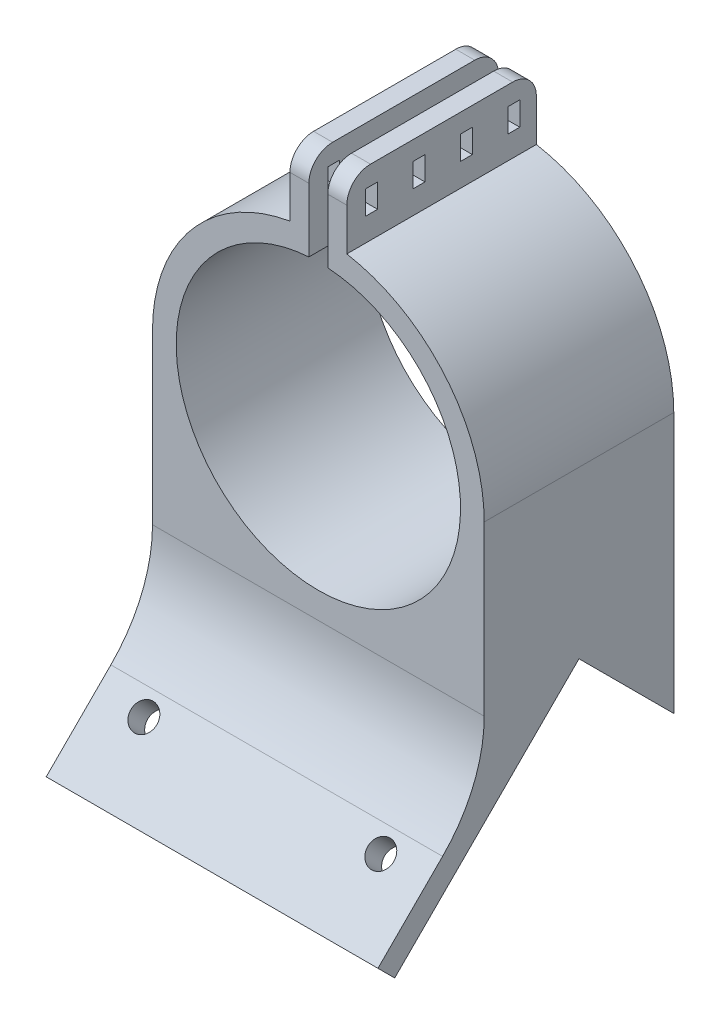
SolidWorks part; units mm, degrees
ref_plane "Plan de face" through (0, 0, 0) normal (0, 0, 1) x (1, 0, 0)
ref_plane "Plan de dessus" through (0, 0, 0) normal (0, 1, 0) x (1, 0, 0)
ref_plane "Plan de droite" through (0, 0, 0) normal (1, 0, 0) x (0, 0, -1)
sketch "Esquisse1" plane through (0, 0, 0) normal (0, 0, 1) x (1, 0, 0)
  circle A0 centre (0, 0) radius 35
  dimension "D1" = 70
extrude "Boss.-Extru.1" add sketch "Esquisse1" along normal blind 40
sketch "Esquisse6" plane through (0, 0, 0) normal (0, 1, 0) x (1, 0, 0)
  line L1 (-35, -40) -> (35, -40)
  line L2 (-35, -40) -> (-35, 0)
  line L3 (-35, 0) -> (35, 0)
  line L4 (35, -40) -> (35, 0)
extrude "Boss.-Extru.3" add sketch "Esquisse6" against normal blind 70
sketch "Esquisse2" plane through (0, 0, 40) normal (0, 0, 1) x (1, 0, 0)
  circle A0 centre (0, 0) radius 30
  dimension "D1" = 60
extrude "Enlèv. mat.-Extru.1" cut sketch "Esquisse2" against normal blind 40
sketch "Esquisse3" plane through (0, 0, 0) normal (0, 0, 1) x (1, 0, 0)
  line L2 (-6, 29.3939) -> (-6, 48.3939)
  line L3 (-6, 48.3939) -> (6, 48.3939)
  line L4 (6, 29.3939) -> (6, 48.3939)
  circle A1 centre (0, 0) radius 30 construction
  arc A2 (6, 29.3939) -> (-6, 29.3939) centre (0, 0) ccw
  dimension "D1" = 12
  dimension "D2" = 19
  dimension "D3" = 6
extrude "Boss.-Extru.2" add sketch "Esquisse3" along normal blind 40
sketch "Esquisse4" plane through (0, 0, 40) normal (0, 0, 1) x (1, 0, 0)
  line L0 (6, 48.3939) -> (-6, 48.3939) construction
  line L1 (-2, 48.3939) -> (2, 48.3939)
  line L2 (-2, 48.3939) -> (-2, 28.3939)
  line L3 (-2, 28.3939) -> (2, 28.3939)
  line L4 (2, 48.3939) -> (2, 28.3939)
  line L5 (-6, 48.3939) -> (-6, 34.4819) construction
  dimension "D1" = 4
  dimension "D2" = 4
  dimension "D3" = 20
extrude "Enlèv. mat.-Extru.2" cut sketch "Esquisse4" against normal blind 40
sketch "Esquisse5" plane through (6, 0, 0) normal (1, 0, 0) x (0, 0, -1)
  line L0 (-40, 48.3939) -> (0, 48.3939) construction
  line L1 (-36, 44.3939) -> (-33.5, 44.3939)
  line L2 (-36, 44.3939) -> (-36, 39.3939)
  line L3 (-36, 39.3939) -> (-33.5, 39.3939)
  line L4 (-33.5, 44.3939) -> (-33.5, 39.3939)
  line L5 (-40, 34.4819) -> (-40, 48.3939) construction
  dimension "D1" = 5
  dimension "D2" = 2.5
  dimension "D3" = 4
  dimension "D4" = 4
extrude "Enlèv. mat.-Extru.3" cut sketch "Esquisse5" against normal through all
pattern_linear "Répétition linéaire1" count 4 spacing 10 along (0, 0, -1) of "Enlèv. mat.-Extru.3"
sketch "Esquisse7" plane through (-35, 0, 0) normal (-1, 0, 0) x (0, 0, 1)
  line L0 (-15, -70) -> (20, -35)
  line L1 (0, -70) -> (40, -70) construction
  line L2 (20, -35) -> (55, -70)
  line L3 (55, -70) -> (-15, -70)
  line L4 (40, -70) -> (40, 0) construction
  dimension "D1" = 35
  dimension "D2" = 20
  dimension "D3" = 90
  dimension "D4" = 45
extrude "Enlèv. mat.-Extru.4" cut sketch "Esquisse7" against normal through all
sketch "Esquisse8" plane through (0, -7.5, -7.5) normal (0, -0.7071, -0.7071) x (1, 0, 0)
  line L0 (35, 67.1751) -> (35, 38.8909) construction
  line L1 (-35, 38.8909) -> (35, 38.8909)
  line L2 (-35, 38.8909) -> (-35, 93.8909)
  line L3 (-35, 93.8909) -> (35, 93.8909)
  line L4 (35, 38.8909) -> (35, 93.8909)
  dimension "D1" = 0
  dimension "D2" = 55
extrude "Boss.-Extru.4" add sketch "Esquisse8" against normal blind 5
hole_wizard "Dégagement M51" positions "Esquisse9" profile "Esquisse10" hole size "M5" standard "ISO" end condition through all
sketch "Esquisse9" plane through (0, -3.9645, -3.9645) normal (0, 0.7071, 0.7071) x (1, 0, 0)
  line L0 (35, -93.8909) -> (-35, -93.8909) construction
  line L1 (35, -62.1751) -> (35, -93.8909) construction
  line L2 (-35, -93.8909) -> (-35, -62.1751) construction
  point P0 (-25, -78.8909)
  point P2 (25, -78.8909)
  dimension "D1" = 15
  dimension "D2" = 15
  dimension "D3" = 10
  dimension "D4" = 10
sketch "Esquisse10" plane through (-25, -59.7487, 51.8198) normal (1, 0, 0) x (0, -0.7071, 0.7071)
  line L0 (0, 0) -> (0, 46.6421)
  line L1 (0, 46.6421) -> (2.75, 46.6421)
  line L2 (2.75, 46.6421) -> (2.75, 0)
  line L5 (2.75, 0) -> (0, 0)
  line L11 (0, -6.35) -> (0, 107.95) construction
  dimension "Diamètre du perçage jusqu'au prochain" = 5.5
  dimension "Profondeur du perçage jusqu'au prochain" = 46.6421
fillet "Congé1" radius 30 1 edges at (0, -47.9289, 40)
fillet "Congé2" radius 5 4 edges at (-4, 48.3939, 40) (-4, 48.3939, 0) (4, 48.3939, 0) (4, 48.3939, 40)
